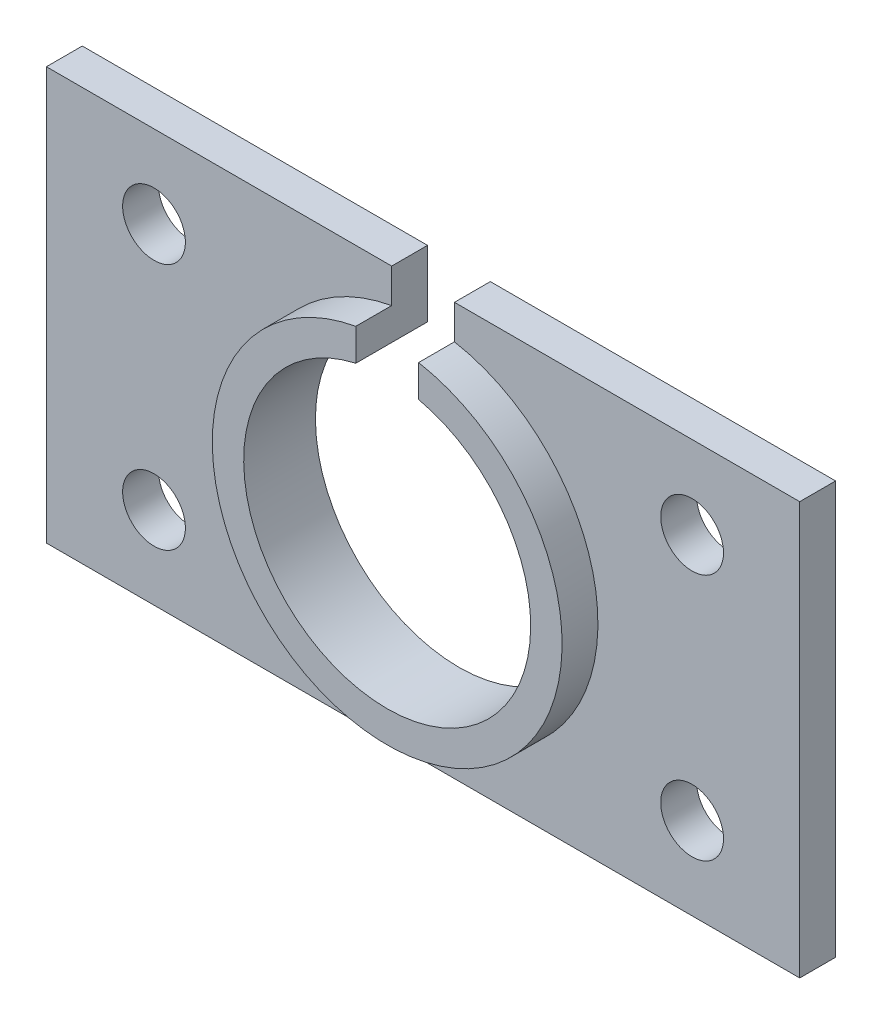
SolidWorks part; units mm, degrees
ref_plane "前视基准面" through (0, 0, 0) normal (0, 0, 1) x (1, 0, 0)
ref_plane "上视基准面" through (0, 0, 0) normal (0, 1, 0) x (1, 0, 0)
ref_plane "右视基准面" through (0, 0, 0) normal (1, 0, 0) x (0, 0, -1)
sketch "草图1" plane through (0, 0, 0) normal (0, 0, 1) x (1, 0, 0)
  circle B0 centre (25, 38.5) radius 5
  circle B1 centre (25, 38.5) radius 10
  circle B2 centre (10, 45.4) radius 1.25
  line B3 (0, 50) -> (50, 50)
  line B4 (0, 0) -> (0, 50)
  circle B5 centre (40, 31.6) radius 1.25
  line B6 (50, 50) -> (50, 0)
  line B7 (50, 0) -> (0, 0)
  circle B8 centre (17.5, 5) radius 1.25
  circle B9 centre (40, 45.4) radius 1.25
  circle B10 centre (10, 31.6) radius 1.25
  circle B11 centre (32.5, 21) radius 1.25
sketch_block_instance "top-1"
sketch_block "top"
sketch "草图2" plane through (0, 0, 0) normal (0, 0, 1) x (1, 0, 0)
  line L5 (0, 50) -> (50, 50) construction
  line L6 (4, 50) -> (46, 50)
  line L7 (4, 50) -> (4, 27)
  line L8 (4, 27) -> (46, 27)
  line L9 (46, 50) -> (46, 27)
  line L10 (25, 27) -> (25, 0) construction
  line L11 (50, 0) -> (0, 0) construction
  dimension "D1" = 42
  dimension "D2" = 23
extrude "凸台-拉伸1" add sketch "草图2" along normal blind 2
sketch "草图3" plane through (0, 0, 2) normal (0, 0, 1) x (1, 0, 0)
  circle A0 centre (25, 38.5) radius 9.75
  dimension "D1" = 19.5
extrude "凸台-拉伸2" add sketch "草图3" along normal blind 2
sketch "草图4" plane through (0, 0, 4) normal (0, 0, 1) x (1, 0, 0)
  circle A0 centre (25, 38.5) radius 8
  dimension "D1" = 16
extrude "切除-拉伸1" cut sketch "草图4" against normal through all
sketch "草图5" plane through (0, 0, 0) normal (0, 0, -1) x (-1, 0, 0)
  circle A0 centre (-40, 45.4) radius 1.75
  circle A1 centre (-40, 31.6) radius 1.75
  circle A2 centre (-10, 31.6) radius 1.75
  circle A3 centre (-10, 45.4) radius 1.75
  dimension "D1" = 3.5
extrude "切除-拉伸2" cut sketch "草图5" against normal through all and the other way through all
sketch "草图7" plane through (0, 0, 0) normal (0, 0, -1) x (-1, 0, 0)
  line L0 (-25, 50) -> (-25, 54.1149) construction
  line L1 (-26.75, 54.1149) -> (-23.25, 54.1149)
  line L2 (-26.75, 54.1149) -> (-26.75, 39.6635)
  line L3 (-26.75, 39.6635) -> (-23.25, 39.6635)
  line L4 (-23.25, 54.1149) -> (-23.25, 39.6635)
  line L5 (-46, 50) -> (-4, 50) construction
  dimension "D1" = 3.5
extrude "切除-拉伸4" cut sketch "草图7" against normal up to next
